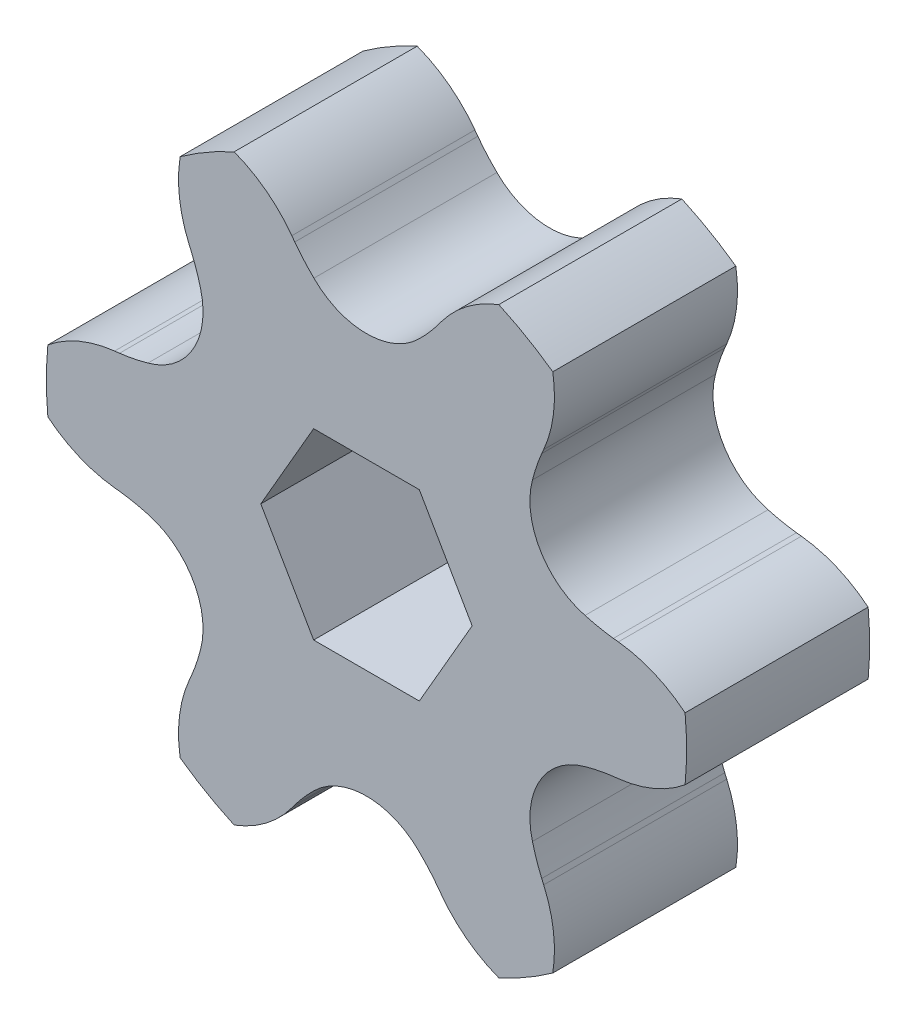
SolidWorks part; units mm, degrees
ref_plane "Front Plane" through (0, 0, 0) normal (0, 0, 1) x (1, 0, 0)
ref_plane "Top Plane" through (0, 0, 0) normal (0, 1, 0) x (1, 0, 0)
ref_plane "Right Plane" through (0, 0, 0) normal (1, 0, 0) x (0, 0, -1)
ref_plane "Plane1" through (0, 0, 4.2926) normal (0, 0, 1) x (1, 0, 0)
sketch "Sketch1" plane through (0, 0, 4.2926) normal (0, 0, 1) x (1, 0, 0)
  line L0 (-6.1484, 6.5397) -> (-6.0793, 6.382)
  line L1 (-8.5666, 2.0738) -> (-8.7377, 2.0548)
  line L2 (-8.7377, -2.0548) -> (-8.5666, -2.0738)
  line L3 (-6.0793, -6.382) -> (-6.1484, -6.5397)
  line L4 (-2.5893, -8.5945) -> (-2.4873, -8.4558)
  line L5 (2.4873, -8.4558) -> (2.5893, -8.5945)
  line L6 (6.1484, -6.5397) -> (6.0793, -6.382)
  line L7 (8.5666, -2.0738) -> (8.7377, -2.0548)
  line L8 (8.7377, 2.0548) -> (8.5666, 2.0738)
  line L9 (6.0793, 6.382) -> (6.1484, 6.5397)
  line L10 (2.5893, 8.5945) -> (2.4873, 8.4558)
  line L11 (-2.4873, 8.4558) -> (-2.5893, 8.5945)
  arc A0 (-4.5903, 10.1134) -> (-6.4633, 9.032) centre (0, 0) ccw
  arc A1 (-6.4633, 9.032) -> (-6.1484, 6.5397) centre (-2.0897, 8.3185) ccw
  arc A2 (-6.0793, 6.382) -> (-5.7574, 5.4301) centre (-12.2045, 3.7803) cw
  arc A3 (-5.7574, 5.4301) -> (-7.5813, 2.271) centre (-8.2489, 4.7625) cw
  arc A4 (-7.5813, 2.271) -> (-8.5666, 2.0738) centre (-9.3761, 8.6792) cw
  arc A5 (-8.7377, 2.0548) -> (-11.0536, 1.0813) centre (-8.2489, -2.3495) ccw
  arc A6 (-11.0536, 1.0813) -> (-11.0536, -1.0813) centre (0, 0) ccw
  arc A7 (-11.0536, -1.0813) -> (-8.7377, -2.0548) centre (-8.2489, 2.3495) ccw
  arc A8 (-8.5666, -2.0738) -> (-7.5813, -2.271) centre (-9.3761, -8.6792) cw
  arc A9 (-7.5813, -2.271) -> (-5.7574, -5.4301) centre (-8.2489, -4.7625) cw
  arc A10 (-5.7574, -5.4301) -> (-6.0793, -6.382) centre (-12.2045, -3.7803) cw
  arc A11 (-6.1484, -6.5397) -> (-6.4633, -9.032) centre (-2.0897, -8.3185) ccw
  arc A12 (-6.4633, -9.032) -> (-4.5903, -10.1134) centre (0, 0) ccw
  arc A13 (-4.5903, -10.1134) -> (-2.5893, -8.5945) centre (-6.1592, -5.969) ccw
  arc A14 (-2.4873, -8.4558) -> (-1.8239, -7.7011) centre (2.8284, -12.4596) cw
  arc A15 (-1.8239, -7.7011) -> (1.8239, -7.7011) centre (0, -9.525) cw
  arc A16 (1.8239, -7.7011) -> (2.4873, -8.4558) centre (-2.8284, -12.4596) cw
  arc A17 (2.5893, -8.5945) -> (4.5903, -10.1134) centre (6.1592, -5.969) ccw
  arc A18 (4.5903, -10.1134) -> (6.4633, -9.032) centre (0, 0) ccw
  arc A19 (6.4633, -9.032) -> (6.1484, -6.5397) centre (2.0897, -8.3185) ccw
  arc A20 (6.0793, -6.382) -> (5.7574, -5.4301) centre (12.2045, -3.7803) cw
  arc A21 (5.7574, -5.4301) -> (7.5813, -2.271) centre (8.2489, -4.7625) cw
  arc A22 (7.5813, -2.271) -> (8.5666, -2.0738) centre (9.3761, -8.6792) cw
  arc A23 (8.7377, -2.0548) -> (11.0536, -1.0813) centre (8.2489, 2.3495) ccw
  arc A24 (11.0536, -1.0813) -> (11.0536, 1.0813) centre (0, 0) ccw
  arc A25 (11.0536, 1.0813) -> (8.7377, 2.0548) centre (8.2489, -2.3495) ccw
  arc A26 (8.5666, 2.0738) -> (7.5813, 2.271) centre (9.3761, 8.6792) cw
  arc A27 (7.5813, 2.271) -> (5.7574, 5.4301) centre (8.2489, 4.7625) cw
  arc A28 (5.7574, 5.4301) -> (6.0793, 6.382) centre (12.2045, 3.7803) cw
  arc A29 (6.1484, 6.5397) -> (6.4633, 9.032) centre (2.0897, 8.3185) ccw
  arc A30 (6.4633, 9.032) -> (4.5903, 10.1134) centre (0, 0) ccw
  arc A31 (4.5903, 10.1134) -> (2.5893, 8.5945) centre (6.1592, 5.969) ccw
  arc A32 (2.4873, 8.4558) -> (1.8239, 7.7011) centre (-2.8284, 12.4596) cw
  arc A33 (1.8239, 7.7011) -> (-1.8239, 7.7011) centre (0, 9.525) cw
  arc A34 (-1.8239, 7.7011) -> (-2.4873, 8.4558) centre (2.8284, 12.4596) cw
  arc A35 (-2.5893, 8.5945) -> (-4.5903, 10.1134) centre (-6.1592, 5.969) ccw
extrude "Boss-Extrude1" add sketch "Sketch1" against normal blind 6.35
sketch "Sketch2" plane through (0, 0, 4.2926) normal (0, 0, 1) x (1, 0, 0)
  line L1 (3.6662, 0) -> (1.8331, 3.175)
  line L2 (1.8331, 3.175) -> (-1.8331, 3.175)
  line L3 (-1.8331, 3.175) -> (-3.6662, 0)
  line L4 (-3.6662, 0) -> (-1.8331, -3.175)
  line L5 (-1.8331, -3.175) -> (1.8331, -3.175)
  line L6 (1.8331, -3.175) -> (3.6662, 0)
  circle A0 centre (0, 0) radius 3.175 construction
  dimension "D1" = 6.35
extrude "Cut-Extrude1" cut sketch "Sketch2" against normal through all
